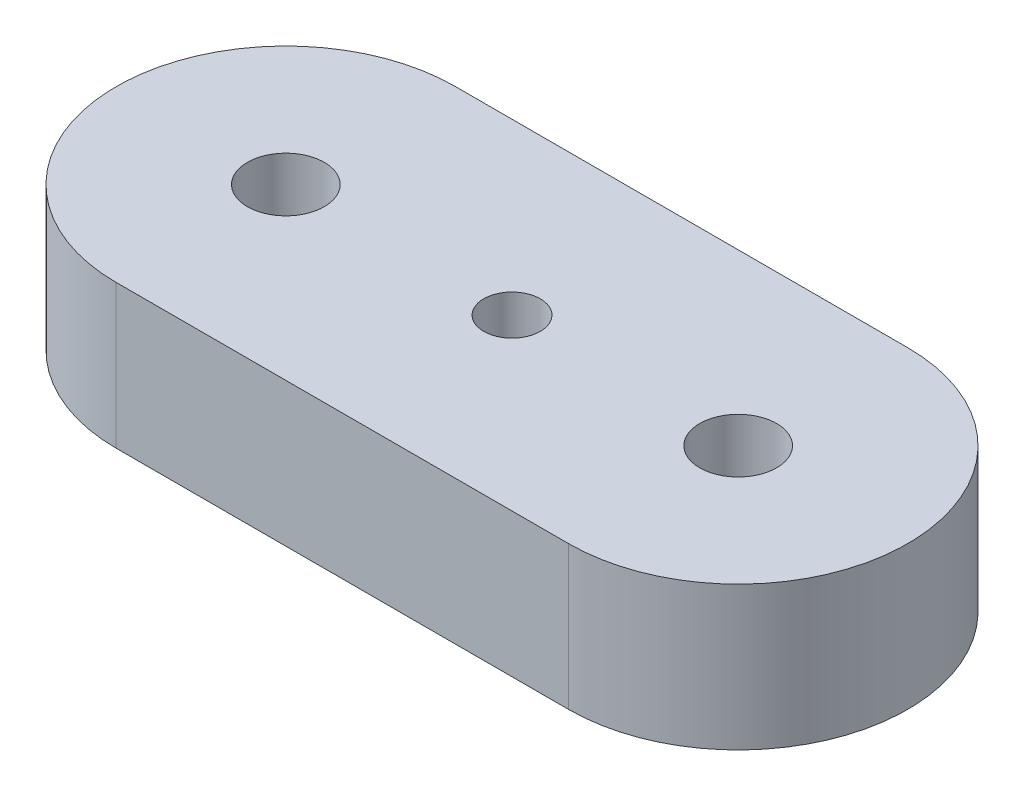
SolidWorks part; units mm, degrees
ref_plane "Front Plane" through (0, 0, 0) normal (0, 0, 1) x (1, 0, 0)
ref_plane "Top Plane" through (0, 0, 0) normal (0, 1, 0) x (1, 0, 0)
ref_plane "Right Plane" through (0, 0, 0) normal (1, 0, 0) x (0, 0, -1)
sketch "Sketch1" plane through (0, 0, 0) normal (0, 1, 0) x (1, 0, 0)
  line L1 (0, 0) -> (20, 0)
  line L3 (0, 15) -> (20, 15)
  arc A0 (0, 15) -> (0, 0) centre (0, 7.5) ccw
  arc A1 (20, 15) -> (20, 0) centre (20, 7.5) cw
  dimension "D1" = 15
  dimension "D2" = 20
extrude "Boss-Extrude1" add sketch "Sketch1" along normal blind 6.35
hole_wizard "M3 Clearance Hole1" positions "3DSketch2" profile "Sketch3" hole size "M3" standard "ANSI Metric" end condition through all
sketch3d "3DSketch2"
  arc A1 (0, 6.35, -15) -> (0, 6.35, 0) centre (0, 6.35, -7.5) ccw construction
  arc A2 (20, 6.35, 0) -> (20, 6.35, -15) centre (20, 6.35, -7.5) ccw construction
  point P0 (0, 6.35, -7.5)
  point P2 (20, 6.35, -7.5)
  point P13 (0, 13.85, -7.5)
  point P18 (20, 13.85, -7.5)
sketch "Sketch3" plane through (0, 6.35, -7.5) normal (1, 0, 0) x (0, 0, 1)
  line L0 (0, 0) -> (0, 6.35)
  line L1 (0, 6.35) -> (1.7, 6.35)
  line L2 (1.7, 6.35) -> (1.7, 0)
  line L5 (1.7, 0) -> (0, 0)
  line L11 (0, -6.35) -> (0, 107.95) construction
  dimension "Thru Hole Dia." = 3.4
  dimension "Thru Hole Depth" = 6.35
hole_wizard "Tap Drill for M3x0.5 Tap1" positions "3DSketch3" profile "Sketch5" hole size "M3x0.5" standard "ANSI Metric" end condition through all
sketch3d "3DSketch3"
  line L0 (0, 6.35, -7.5) -> (20, 6.35, -7.5) construction
  line L1 (0, 0, -7.5) -> (0, 6.35, -7.5) construction
  line L2 (20, 0, -7.5) -> (20, 6.35, -7.5) construction
  point P0 (10, 6.35, -7.5)
  point P11 (10, 6.35, -7.5)
sketch "Sketch5" plane through (10, 6.35, -7.5) normal (1, 0, 0) x (0, 0, 1)
  line L0 (0, 0) -> (0, 6.35)
  line L1 (0, 6.35) -> (1.25, 6.35)
  line L2 (1.25, 6.35) -> (1.25, 0)
  line L5 (1.25, 0) -> (0, 0)
  line L11 (0, -6.35) -> (0, 107.95) construction
  dimension "Thru Hole Dia." = 2.5
  dimension "Thru Hole Depth" = 6.35
